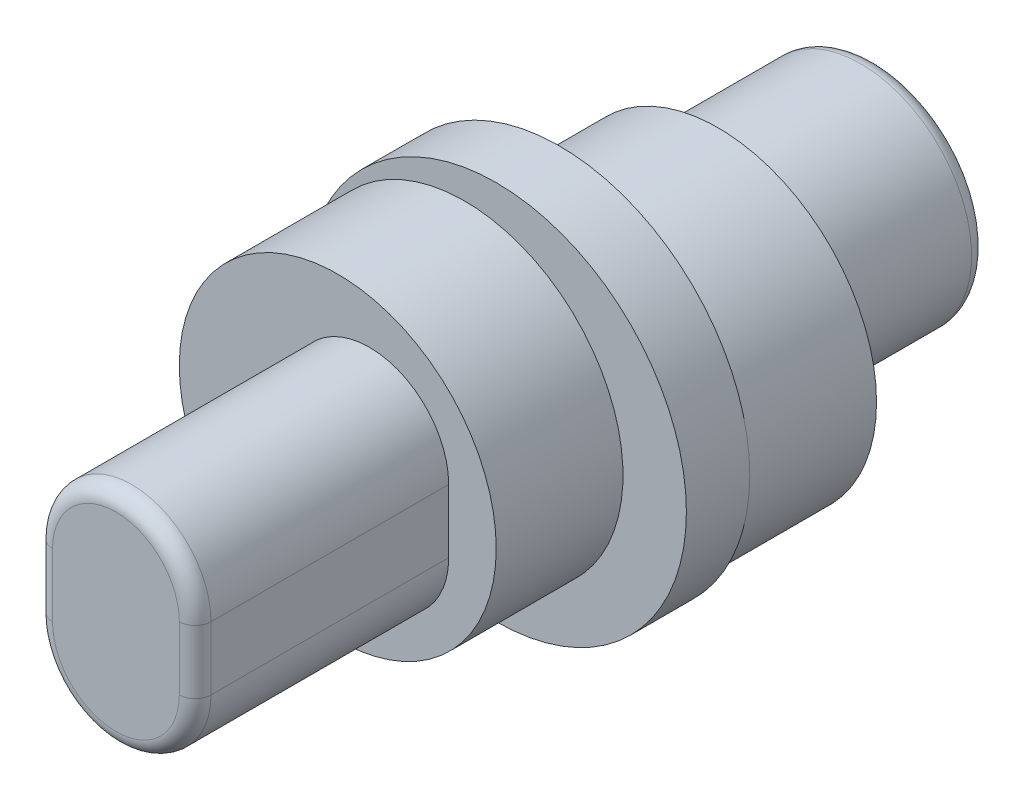
SolidWorks part; units mm, degrees
ref_plane "前视基准面" through (0, 0, 0) normal (0, 0, 1) x (1, 0, 0)
ref_plane "上视基准面" through (0, 0, 0) normal (0, 1, 0) x (1, 0, 0)
ref_plane "右视基准面" through (0, 0, 0) normal (1, 0, 0) x (0, 0, -1)
other "Configuration Table"
sketch "草图1" plane through (0, 0, 0) normal (0, 0, 1) x (1, 0, 0)
  circle A0 centre (-1, 0) radius 5
  dimension "D1" = 10
  dimension "D2" = 1
extrude "凸台-拉伸1" add sketch "草图1" along normal blind 4
sketch "草图2" plane through (0, 0, 0) normal (0, 0, -1) x (-1, 0, 0)
  circle A0 centre (0, 0) radius 6
  dimension "D1" = 12
extrude "凸台-拉伸2" add sketch "草图2" along normal blind 2
sketch "草图3" plane through (0, 0, -2) normal (0, 0, -1) x (-1, 0, 0)
  circle A0 centre (-1, 0) radius 5
  dimension "D2" = 10
  dimension "D1" = 1
extrude "凸台-拉伸3" add sketch "草图3" along normal blind 4
sketch "草图4" plane through (0, 0, 4) normal (0, 0, 1) x (1, 0, 0)
  circle A0 centre (0, 0) radius 3.5
  dimension "D1" = 7
extrude "凸台-拉伸4" add sketch "草图4" along normal blind 8
sketch "草图5" plane through (0, 0, -6) normal (0, 0, -1) x (-1, 0, 0)
  circle A0 centre (0, 0) radius 3.5
  dimension "D1" = 7
extrude "凸台-拉伸5" add sketch "草图5" along normal blind 6
sketch "草图7" plane through (0, 0, 12) normal (0, 0, 1) x (1, 0, 0)
  line L0 (0, -1) -> (0, 1) construction
  line L1 (-2.5, -1) -> (-2.5, 1)
  line L2 (2.5, -1) -> (2.5, 1)
  arc A0 (-2.5, -1) -> (2.5, -1) centre (0, -1) ccw
  arc A1 (2.5, 1) -> (-2.5, 1) centre (0, 1) ccw
  circle A3 centre (0, 0) radius 3.5 construction
  circle A4 centre (0, 0) radius 3.5
  point P2 (0, 0)
  circle M5 centre (0, 0) radius 3.5
  dimension "D1" = 5
extrude "切除-拉伸2" cut sketch "草图7" against normal blind 8 contours A1 L2 A0 M5 | A1 A0 L1 M5
fillet "圆角1" radius 0.5 5 edges at (-2.5, 0, 12) (0, 3.5, 12) (2.5, 0, 12) (0, -3.5, 12) (-3.5, 0, -12)
